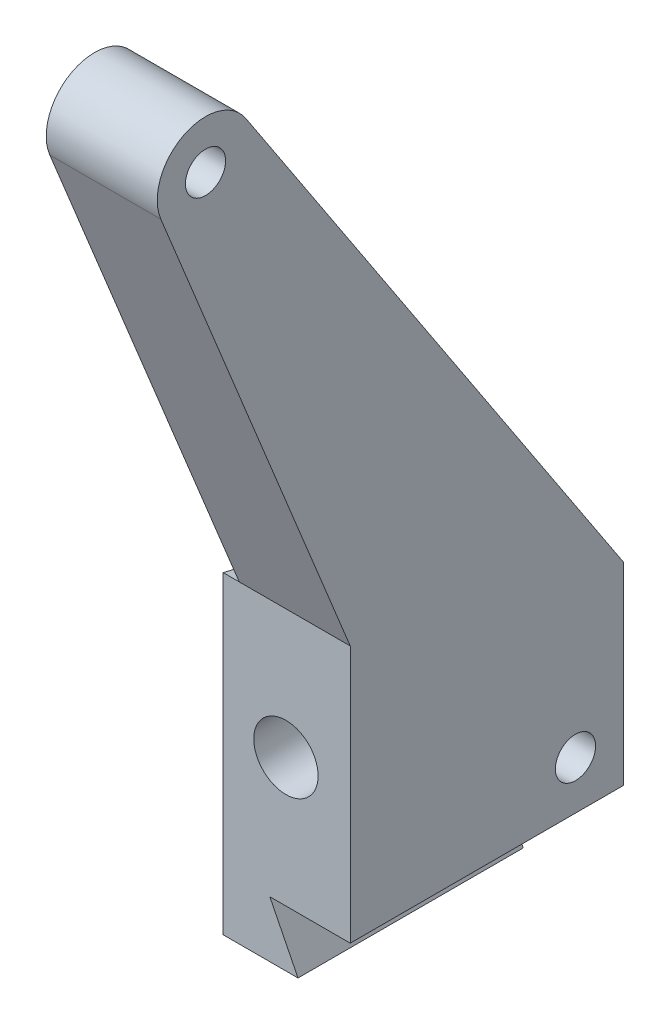
SolidWorks part; units mm, degrees
ref_plane "Front Plane" through (0, 0, 0) normal (0, 0, 1) x (1, 0, 0)
ref_plane "Top Plane" through (0, 0, 0) normal (0, 1, 0) x (1, 0, 0)
ref_plane "Right Plane" through (0, 0, 0) normal (1, 0, 0) x (0, 0, -1)
sketch "Sketch1" plane through (0, 0, 0) normal (1, 0, 0) x (0, 0, -1)
  line L0 (0, 0) -> (0, 16)
  line L1 (0, 16) -> (-23.4951, 51.6508)
  line L2 (-17, 20) -> (-17, 0)
  line L3 (-17, 0) -> (0, 0)
  line L4 (-17, 20) -> (-28.7777, 48.8667)
  arc A0 (-23.4951, 51.6508) -> (-28.7777, 48.8667) centre (-26, 50) ccw
  circle A1 centre (-26, 50) radius 1.25
  dimension "D4" = 6
  dimension "D5" = 9
  dimension "D6" = 50
  dimension "D7" = 2.5
  dimension "D1" = 20
  dimension "D2" = 16
  dimension "D3" = 17
extrude "Boss-Extrude1" add sketch "Sketch1" along normal blind 7.9
sketch "Sketch2" plane through (7.9, 0, 0) normal (1, 0, 0) x (0, 0, -1)
  line L0 (-17, 20) -> (-17, 0) construction
  line L1 (-17, 5) -> (0, 5)
  line L2 (-17, 5) -> (-17, 0)
  line L3 (-17, 0) -> (0, 0)
  line L4 (0, 5) -> (0, 0)
  line L5 (0, 0) -> (0, 16) construction
  dimension "D1" = 5
extrude "Cut-Extrude1" [suppressed] cut sketch "Sketch2" against normal blind 4
sketch "Sketch3" plane through (0, 0, 0) normal (0, 0, -1) x (-1, 0, 0)
  line L0 (-7.9, 0) -> (-4.9, 0)
  line L1 (-7.9, 0) -> (0, 0) construction
  line L2 (-4.9, 0) -> (-2.9, 4)
  line L3 (-2.9, 4) -> (-7.9, 4)
  line L4 (-7.9, 0) -> (-7.9, 16) construction
  line L5 (-7.9, 4) -> (-7.9, 0)
  dimension "D1" = 5
  dimension "D2" = 3
  dimension "D3" = 4
extrude "Cut-Extrude2" cut sketch "Sketch3" against normal through all
sketch "Sketch5" plane through (7.9, 0, 0) normal (1, 0, 0) x (0, 0, -1)
  line L0 (0, 4) -> (0, 16) construction
  line L1 (-17, 4) -> (0, 4) construction
  circle A0 centre (-3, 7) radius 1
  dimension "D1" = 2
  dimension "D3" = 3
  dimension "D2" = 3
hole_wizard "M3x0.5 Tapped Hole1" positions "3DSketch1" profile "Sketch6" tap size "M3x0.5" standard "ANSI Metric" end condition through all
sketch3d "3DSketch1"
  point P0 (7.9, 7, 3)
sketch "Sketch6" plane through (7.9, 7, 3) normal (0, 1, 0) x (0, 0, -1)
  line L0 (0, 0) -> (0, 7.9)
  line L1 (0, 7.9) -> (1.25, 7.9)
  line L2 (1.25, 7.9) -> (1.25, 0)
  line L5 (1.25, 0) -> (0, 0)
  line L11 (0, -6.35) -> (0, 107.95) construction
  dimension "Thread Major Dia." = 2.5
  dimension "Thru Tap Drill Depth" = 7.9
sketch "Sketch7" plane through (0, 0, 0) normal (0, 0, -1) x (-1, 0, 0)
  line L1 (0, 0) -> (-8, 0)
  line L2 (0, 0) -> (0, 0.5)
  line L3 (0, 0.5) -> (-8, 0.5)
  line L4 (-8, 0) -> (-8, 0.5)
  dimension "D1" = 0.5
  dimension "D2" = 8
extrude "Cut-Extrude3" cut sketch "Sketch7" against normal through all
sketch "Sketch8" plane through (0, 0, 17) normal (0, 0, 1) x (1, 0, 0)
  line L0 (2.9, 4) -> (7.9, 4) construction
  line L1 (7.9, 20) -> (7.9, 4) construction
  circle A0 centre (3.9, 12) radius 2
  point P4 (5.4, 4)
  dimension "D1" = 4
  dimension "D2" = 8
  dimension "D3" = 4
extrude "Cut-Extrude4" cut sketch "Sketch8" against normal through all
sketch "Sketch9" plane through (0, 0, 0) normal (0, 0, -1) x (-1, 0, 0)
  line L0 (-4.65, 0.5) -> (-2.9, 4)
  line L1 (-2.9, 4) -> (0, 4)
  line L2 (0, 0.5) -> (0, 16) construction
  line L3 (0, 4) -> (0, 0.5)
  line L4 (0, 0.5) -> (-4.65, 0.5)
extrude "Cut-Extrude5" cut sketch "Sketch9" against normal blind 3
sketch "Sketch11" plane through (0, 0, 0) normal (-1, 0, 0) x (0, 0, 1)
  line L0 (0, 16) -> (17, 20)
  line L1 (17, 20) -> (28.7777, 48.8667)
  line L2 (23.4951, 51.6508) -> (0, 16)
  arc A0 (28.7777, 48.8667) -> (23.4951, 51.6508) centre (26, 50) ccw
extrude "Cut-Extrude6" cut sketch "Sketch11" against normal blind 1
sketch "Sketch14" plane through (1, 0, 0) normal (-1, 0, 0) x (0, 0, 1)
  line L0 (0, 16) -> (15.9581, 40.2144)
  line L1 (23.4951, 51.6508) -> (0, 16) construction
  line L2 (17, 0.5) -> (3, 0.5) construction
  arc A0 (0, 16) -> (15.9581, 40.2144) centre (2.3313, 31.8292) ccw
  dimension "D2" = 16
  dimension "D1" = 29
  dimension "D3" = 15.5
extrude "Cut-Extrude8" cut sketch "Sketch14" against normal mid plane 7.8
